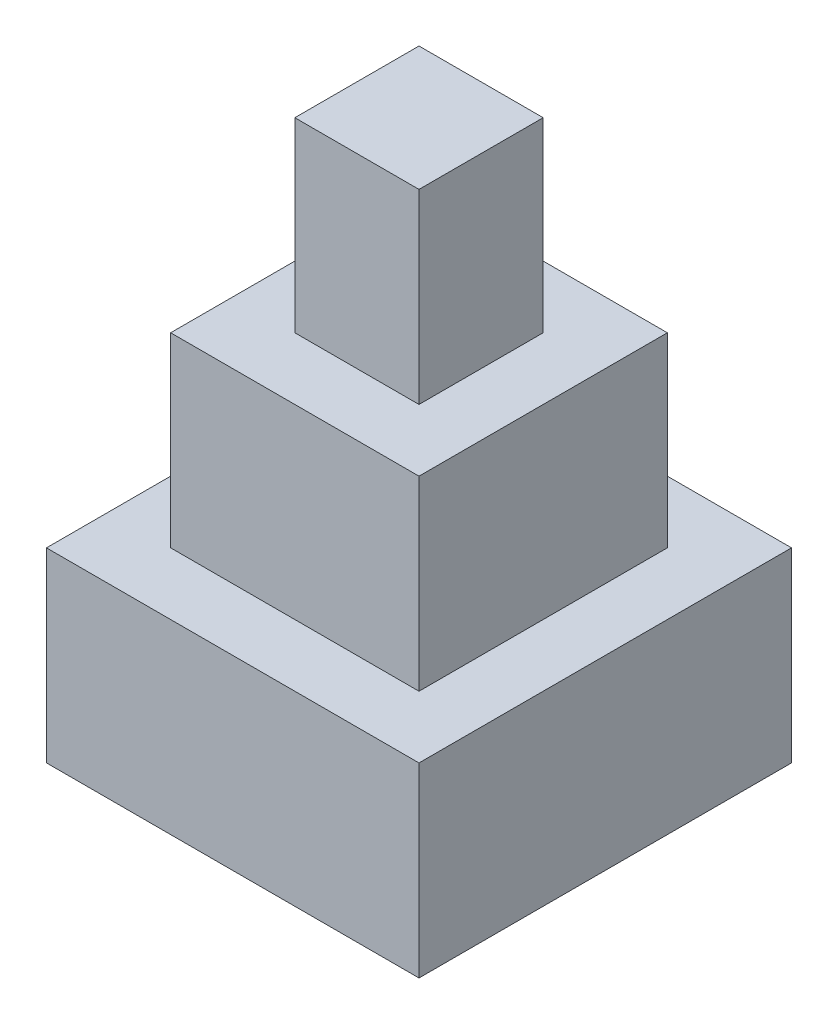
SolidWorks part; units mm, degrees
ref_plane "정면" through (0, 0, 0) normal (0, 0, 1) x (1, 0, 0)
ref_plane "윗면" through (0, 0, 0) normal (0, 1, 0) x (1, 0, 0)
ref_plane "우측면" through (0, 0, 0) normal (1, 0, 0) x (0, 0, -1)
sketch "스케치1" plane through (0, 0, 0) normal (0, 1, 0) x (1, 0, 0)
  line L1 (-55.4032, -37.4638) -> (4.5968, -37.4638)
  line L2 (-55.4032, -37.4638) -> (-55.4032, 22.5362)
  line L3 (-55.4032, 22.5362) -> (4.5968, 22.5362)
  line L4 (4.5968, -37.4638) -> (4.5968, 22.5362)
  line L5 (-55.4032, -37.4638) -> (4.5968, 22.5362) construction
  line L6 (-55.4032, 22.5362) -> (4.5968, -37.4638) construction
  point P0 (-25.4032, -7.4638)
  dimension "D1" = 60
  dimension "D2" = 60
extrude "보스-돌출1" add sketch "스케치1" along normal blind 30 contours L2 L1 L4 L3
sketch "스케치2" plane through (0, 30, 0) normal (0, 1, 0) x (1, 0, 0)
  line L4 (-45.4032, -27.4638) -> (-5.4032, -27.4638)
  line L5 (-45.4032, -27.4638) -> (-45.4032, 12.5362)
  line L6 (-45.4032, 12.5362) -> (-5.4032, 12.5362)
  line L7 (-5.4032, -27.4638) -> (-5.4032, 12.5362)
  line L8 (-45.4032, -27.4638) -> (-5.4032, 12.5362) construction
  line L9 (-45.4032, 12.5362) -> (-5.4032, -27.4638) construction
  point P6 (-25.4032, -7.4638)
extrude "보스-돌출2" add sketch "스케치2" along normal blind 30
sketch "스케치3" plane through (0, 60, 0) normal (0, 1, 0) x (1, 0, 0)
  line L4 (-35.4032, -17.4638) -> (-15.4032, -17.4638)
  line L5 (-35.4032, -17.4638) -> (-35.4032, 2.5362)
  line L6 (-35.4032, 2.5362) -> (-15.4032, 2.5362)
  line L7 (-15.4032, -17.4638) -> (-15.4032, 2.5362)
  line L8 (-35.4032, -17.4638) -> (-15.4032, 2.5362) construction
  line L9 (-35.4032, 2.5362) -> (-15.4032, -17.4638) construction
  point P6 (-25.4032, -7.4638)
extrude "보스-돌출3" add sketch "스케치3" along normal blind 30
